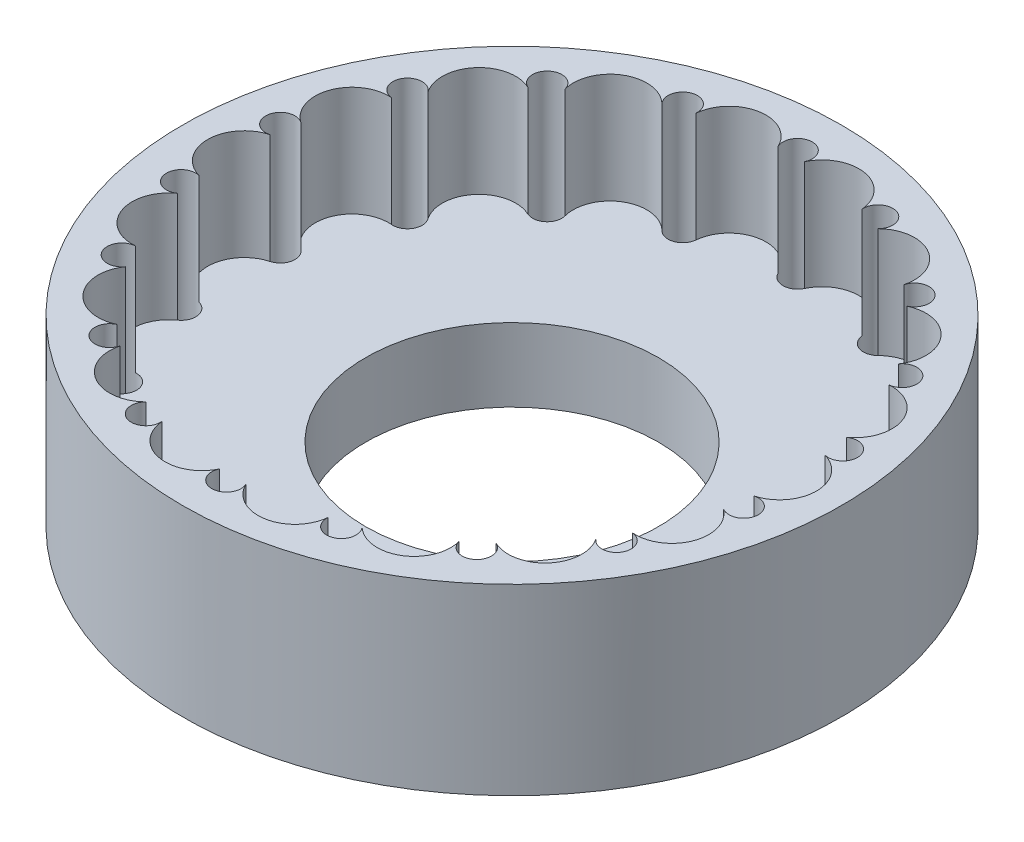
SolidWorks part; units mm, degrees
ref_plane "Front Plane" through (0, 0, 0) normal (0, 0, 1) x (1, 0, 0)
ref_plane "Top Plane" through (0, 0, 0) normal (0, 1, 0) x (1, 0, 0)
ref_plane "Right Plane" through (0, 0, 0) normal (1, 0, 0) x (0, 0, -1)
sketch "Sketch1" plane through (0, 0, 0) normal (0, 1, 0) x (1, 0, 0)
  circle A0 centre (0, 0) radius 39 construction
  circle A1 centre (0, 39) radius 2
  circle A2 centre (13.3388, 36.648) radius 2
  circle A3 centre (25.0687, 29.8757) radius 2
  circle A4 centre (33.775, 19.5) radius 2
  circle A5 centre (38.4075, 6.7723) radius 2
  circle A6 centre (38.4075, -6.7723) radius 2
  circle A7 centre (33.775, -19.5) radius 2
  circle A8 centre (25.0687, -29.8757) radius 2
  circle A9 centre (13.3388, -36.648) radius 2
  circle A10 centre (0, -39) radius 2
  circle A11 centre (-13.3388, -36.648) radius 2
  circle A12 centre (-25.0687, -29.8757) radius 2
  circle A13 centre (-33.775, -19.5) radius 2
  circle A14 centre (-38.4075, -6.7723) radius 2
  circle A15 centre (-38.4075, 6.7723) radius 2
  circle A16 centre (-33.775, 19.5) radius 2
  circle A17 centre (-25.0687, 29.8757) radius 2
  circle A18 centre (-13.3388, 36.648) radius 2
  circle A19 centre (0, 0) radius 45
  circle A20 centre (0, 0) radius 20
  point P42 (0, 0)
  dimension "D1" = 78
  dimension "D2" = 4
  dimension "D4" = 90
  dimension "D3" = 18
extrude "Boss-Extrude1" add sketch "Sketch1" along normal blind 5
sketch "Sketch2" plane through (0, 0, 0) normal (0, -1, 0) x (1, 0, 0)
  circle A0 centre (0, 0) radius 45 construction
  circle A1 centre (0, 0) radius 45
  circle A2 centre (0, 0) radius 20 construction
  circle A3 centre (0, 0) radius 20
extrude "Boss-Extrude2" add sketch "Sketch2" along normal blind 5
sketch "Sketch3" plane through (0, 0, 0) normal (0, 1, 0) x (1, 0, 0)
  circle A0 centre (-33.775, 19.5) radius 2 construction
  circle A1 centre (-38.4075, 6.7723) radius 2 construction
  circle A2 centre (-38.4075, -6.7723) radius 2 construction
  circle A3 centre (-33.775, -19.5) radius 2 construction
  circle A4 centre (-25.0687, -29.8757) radius 2 construction
  circle A5 centre (-13.3388, -36.648) radius 2 construction
  circle A6 centre (0, -39) radius 2 construction
  circle A7 centre (13.3388, -36.648) radius 2 construction
  circle A8 centre (25.0687, -29.8757) radius 2 construction
  circle A9 centre (33.775, -19.5) radius 2 construction
  circle A10 centre (38.4075, -6.7723) radius 2 construction
  circle A11 centre (38.4075, 6.7723) radius 2 construction
  circle A12 centre (33.775, 19.5) radius 2 construction
  circle A13 centre (25.0687, 29.8757) radius 2 construction
  circle A14 centre (13.3388, 36.648) radius 2 construction
  circle A15 centre (0, 39) radius 2 construction
  circle A16 centre (-13.3388, 36.648) radius 2 construction
  circle A17 centre (-25.0687, 29.8757) radius 2 construction
  arc A18 (-33.939, 17.5067) -> (-32.1308, 20.6387) centre (-33.775, 19.5) ccw
  arc A19 (-37.8799, 4.8431) -> (-37.2519, 8.4046) centre (-38.4075, 6.7723) ccw
  arc A20 (-37.2519, -8.4046) -> (-37.8799, -4.8431) centre (-38.4075, -6.7723) ccw
  arc A21 (-32.1308, -20.6387) -> (-33.939, -17.5067) centre (-33.775, -19.5) ccw
  arc A22 (-23.1342, -30.3834) -> (-25.9046, -28.0588) centre (-25.0687, -29.8757) ccw
  arc A23 (-11.3473, -36.4634) -> (-14.7457, -35.2265) centre (-13.3388, -36.648) ccw
  arc A24 (1.8082, -38.1454) -> (-1.8082, -38.1454) centre (0, -39) ccw
  arc A25 (14.7457, -35.2265) -> (11.3473, -36.4634) centre (13.3388, -36.648) ccw
  arc A26 (25.9046, -28.0588) -> (23.1342, -30.3834) centre (25.0687, -29.8757) ccw
  arc A27 (33.939, -17.5067) -> (32.1308, -20.6387) centre (33.775, -19.5) ccw
  arc A28 (37.8799, -4.8431) -> (37.2519, -8.4046) centre (38.4075, -6.7723) ccw
  arc A29 (37.2519, 8.4046) -> (37.8799, 4.8431) centre (38.4075, 6.7723) ccw
  arc A30 (32.1308, 20.6387) -> (33.939, 17.5067) centre (33.775, 19.5) ccw
  arc A31 (23.1342, 30.3834) -> (25.9046, 28.0588) centre (25.0687, 29.8757) ccw
  arc A32 (11.3473, 36.4634) -> (14.7457, 35.2265) centre (13.3388, 36.648) ccw
  arc A33 (-1.8082, 38.1454) -> (1.8082, 38.1454) centre (0, 39) ccw
  arc A34 (-14.7457, 35.2265) -> (-11.3473, 36.4634) centre (-13.3388, 36.648) ccw
  arc A35 (-25.9046, 28.0588) -> (-23.1342, 30.3834) centre (-25.0687, 29.8757) ccw
  arc A36 (-11.3473, 36.4634) -> (-1.8082, 38.1454) centre (-6.3478, 36) cw
  arc A37 (1.8082, 38.1454) -> (11.3473, 36.4634) centre (6.3478, 36) cw
  arc A38 (14.7457, 35.2265) -> (23.1342, 30.3834) centre (18.2777, 31.6579) cw
  arc A39 (25.9046, 28.0588) -> (32.1308, 20.6387) centre (28.003, 23.4973) cw
  arc A40 (33.939, 17.5067) -> (37.2519, 8.4046) centre (34.3508, 12.5027) cw
  arc A41 (37.8799, 4.8431) -> (37.8799, -4.8431) centre (36.5554, 0) cw
  arc A42 (37.2519, -8.4046) -> (33.939, -17.5067) centre (34.3508, -12.5027) cw
  arc A43 (32.1308, -20.6387) -> (25.9046, -28.0588) centre (28.003, -23.4973) cw
  arc A44 (23.1342, -30.3834) -> (14.7457, -35.2265) centre (18.2777, -31.6579) cw
  arc A45 (11.3473, -36.4634) -> (1.8082, -38.1454) centre (6.3478, -36) cw
  arc A46 (-1.8082, -38.1454) -> (-11.3473, -36.4634) centre (-6.3478, -36) cw
  arc A47 (-14.7457, -35.2265) -> (-23.1342, -30.3834) centre (-18.2777, -31.6579) cw
  arc A48 (-25.9046, -28.0588) -> (-32.1308, -20.6387) centre (-28.003, -23.4973) cw
  arc A49 (-33.939, -17.5067) -> (-37.2519, -8.4046) centre (-34.3508, -12.5027) cw
  arc A50 (-37.8799, -4.8431) -> (-37.8799, 4.8431) centre (-36.5554, 0) cw
  arc A51 (-37.2519, 8.4046) -> (-33.939, 17.5067) centre (-34.3508, 12.5027) cw
  arc A52 (-32.1308, 20.6387) -> (-25.9046, 28.0588) centre (-28.003, 23.4973) cw
  arc A53 (-23.1342, 30.3834) -> (-14.7457, 35.2265) centre (-18.2777, 31.6579) cw
  circle A54 centre (0, 0) radius 45 construction
  circle A55 centre (0, 0) radius 45
  point P111 (0, 0)
  dimension "D1" = 3
  dimension "D2" = 18
extrude "Boss-Extrude3" add sketch "Sketch3" along normal blind 20
sketch "Sketch4" plane through (0, 20, 0) normal (0, 1, 0) x (1, 0, 0)
  circle A0 centre (0, 39) radius 2
  circle A1 centre (13.3388, 36.648) radius 2
  circle A2 centre (25.0687, 29.8757) radius 2
  circle A3 centre (33.775, 19.5) radius 2
  circle A4 centre (38.4075, 6.7723) radius 2
  circle A5 centre (38.4075, -6.7723) radius 2
  circle A6 centre (33.775, -19.5) radius 2
  circle A7 centre (25.0687, -29.8757) radius 2
  circle A8 centre (13.3388, -36.648) radius 2
  circle A9 centre (0, -39) radius 2
  circle A10 centre (-13.3388, -36.648) radius 2
  circle A11 centre (-25.0687, -29.8757) radius 2
  circle A12 centre (-33.775, -19.5) radius 2
  circle A13 centre (-38.4075, -6.7723) radius 2
  circle A14 centre (-38.4075, 6.7723) radius 2
  circle A15 centre (-33.775, 19.5) radius 2
  circle A16 centre (-25.0687, 29.8757) radius 2
  circle A17 centre (-13.3388, 36.648) radius 2
  point P39 (0, 0)
  dimension "D1" = 4
  dimension "D2" = 18
extrude "Cut-Extrude1" cut sketch "Sketch4" against normal blind 20
